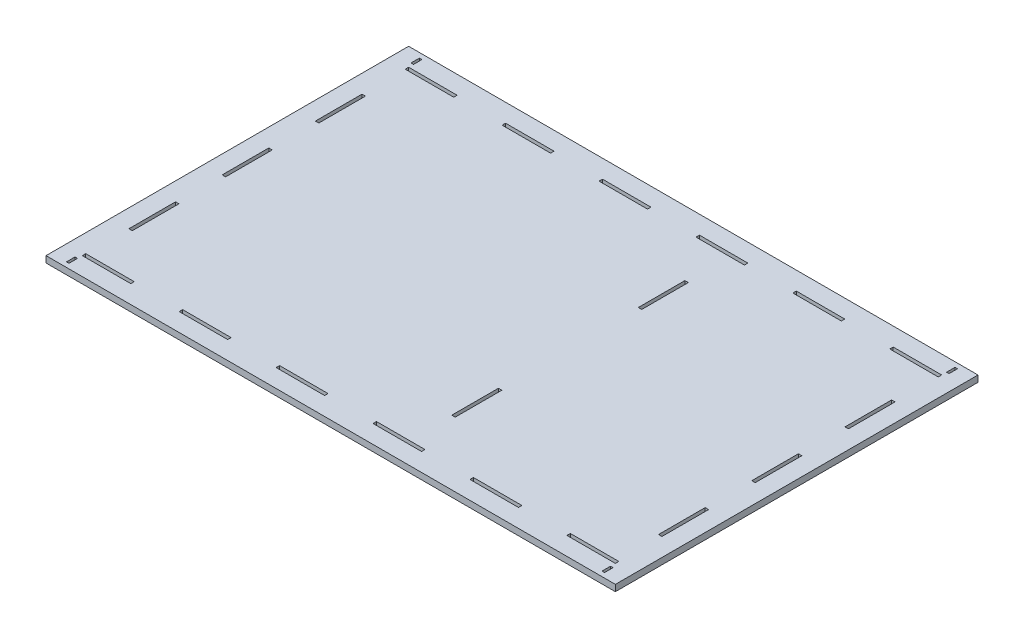
SolidWorks part; units mm, degrees
ref_plane "Front Plane" through (0, 0, 0) normal (0, 0, 1) x (1, 0, 0)
ref_plane "Top Plane" through (0, 0, 0) normal (0, 1, 0) x (1, 0, 0)
ref_plane "Right Plane" through (0, 0, 0) normal (1, 0, 0) x (0, 0, -1)
sketch "Sketch2" plane through (0, 0, 0) normal (0, 1, 0) x (1, 0, 0)
  line L0 (-230.0986, 0) -> (230.0986, 0) construction
  line L1 (-230.0986, 139.7) -> (230.0986, 139.7)
  line L2 (-230.0986, 139.7) -> (-230.0986, -139.7)
  line L3 (-230.0986, -139.7) -> (230.0986, -139.7)
  line L4 (230.0986, 139.7) -> (230.0986, -139.7)
  line L5 (0, 139.7) -> (0, -139.7) construction
  line L6 (-148.3337, -139.7) -> (-148.3337, -142.6972)
  line L15 (-230.0986, 142.6972) -> (-233.0958, 142.6972)
  line L16 (-230.0986, 142.6972) -> (-230.0986, 101.9266)
  line L17 (-230.0986, 101.9266) -> (-233.0958, 101.9266)
  line L18 (-233.0958, 142.6972) -> (-233.0958, 101.9266)
  line L19 (230.0986, 101.9266) -> (233.0958, 101.9266)
  line L20 (230.0986, 101.9266) -> (230.0986, 142.6972)
  line L21 (230.0986, 142.6972) -> (233.0958, 142.6972)
  line L22 (233.0958, 101.9266) -> (233.0958, 142.6972)
  line L23 (-190.7147, -139.7) -> (-233.0958, -139.7)
  line L24 (-190.7147, -139.7) -> (-190.7147, -142.6972)
  line L25 (-190.7147, -142.6972) -> (-233.0958, -142.6972)
  line L26 (-233.0958, -139.7) -> (-233.0958, -142.6972)
  line L27 (-233.0958, 142.6972) -> (-190.7147, 142.6972)
  line L28 (-233.0958, 142.6972) -> (-233.0958, 139.7)
  line L29 (-233.0958, 139.7) -> (-190.7147, 139.7)
  line L30 (-190.7147, 142.6972) -> (-190.7147, 139.7)
  line L31 (-148.3337, -139.7) -> (-190.7147, -139.7)
  line L32 (-190.7147, -139.7) -> (-190.7147, -142.6972)
  line L33 (-148.3337, -142.6972) -> (-190.7147, -142.6972)
  line L34 (-190.7147, 142.6972) -> (-190.7147, 139.7)
  line L35 (-190.7147, 142.6972) -> (-148.3337, 142.6972)
  line L36 (-148.3337, 142.6972) -> (-148.3337, 139.7)
  line L37 (-190.7147, 139.7) -> (-148.3337, 139.7)
  line L38 (-105.9526, -139.7) -> (-105.9526, -142.6972)
  line L39 (-105.9526, -139.7) -> (-148.3337, -139.7)
  line L40 (-148.3337, -139.7) -> (-148.3337, -142.6972)
  line L41 (-105.9526, -142.6972) -> (-148.3337, -142.6972)
  line L42 (-148.3337, 142.6972) -> (-148.3337, 139.7)
  line L43 (-148.3337, 142.6972) -> (-105.9526, 142.6972)
  line L44 (-105.9526, 142.6972) -> (-105.9526, 139.7)
  line L45 (-148.3337, 139.7) -> (-105.9526, 139.7)
  line L46 (-63.5716, -139.7) -> (-63.5716, -142.6972)
  line L47 (-63.5716, -139.7) -> (-105.9526, -139.7)
  line L48 (-105.9526, -139.7) -> (-105.9526, -142.6972)
  line L49 (-63.5716, -142.6972) -> (-105.9526, -142.6972)
  line L50 (-105.9526, 142.6972) -> (-105.9526, 139.7)
  line L51 (-105.9526, 142.6972) -> (-63.5716, 142.6972)
  line L52 (-63.5716, 142.6972) -> (-63.5716, 139.7)
  line L53 (-105.9526, 139.7) -> (-63.5716, 139.7)
  line L54 (-21.1905, -139.7) -> (-21.1905, -142.6972)
  line L55 (-21.1905, -139.7) -> (-63.5716, -139.7)
  line L56 (-63.5716, -139.7) -> (-63.5716, -142.6972)
  line L57 (-21.1905, -142.6972) -> (-63.5716, -142.6972)
  line L58 (-63.5716, 142.6972) -> (-63.5716, 139.7)
  line L59 (-63.5716, 142.6972) -> (-21.1905, 142.6972)
  line L60 (-21.1905, 142.6972) -> (-21.1905, 139.7)
  line L61 (-63.5716, 139.7) -> (-21.1905, 139.7)
  line L62 (21.1905, -139.7) -> (21.1905, -142.6972)
  line L63 (21.1905, -139.7) -> (-21.1905, -139.7)
  line L64 (-21.1905, -139.7) -> (-21.1905, -142.6972)
  line L65 (21.1905, -142.6972) -> (-21.1905, -142.6972)
  line L66 (-21.1905, 142.6972) -> (-21.1905, 139.7)
  line L67 (-21.1905, 142.6972) -> (21.1905, 142.6972)
  line L68 (21.1905, 142.6972) -> (21.1905, 139.7)
  line L69 (-21.1905, 139.7) -> (21.1905, 139.7)
  line L70 (63.5716, -139.7) -> (63.5716, -142.6972)
  line L71 (63.5716, -139.7) -> (21.1905, -139.7)
  line L72 (21.1905, -139.7) -> (21.1905, -142.6972)
  line L73 (63.5716, -142.6972) -> (21.1905, -142.6972)
  line L74 (21.1905, 142.6972) -> (21.1905, 139.7)
  line L75 (21.1905, 142.6972) -> (63.5716, 142.6972)
  line L76 (63.5716, 142.6972) -> (63.5716, 139.7)
  line L77 (21.1905, 139.7) -> (63.5716, 139.7)
  line L78 (105.9526, -139.7) -> (105.9526, -142.6972)
  line L79 (105.9526, -139.7) -> (63.5716, -139.7)
  line L80 (63.5716, -139.7) -> (63.5716, -142.6972)
  line L81 (105.9526, -142.6972) -> (63.5716, -142.6972)
  line L82 (63.5716, 142.6972) -> (63.5716, 139.7)
  line L83 (63.5716, 142.6972) -> (105.9526, 142.6972)
  line L84 (105.9526, 142.6972) -> (105.9526, 139.7)
  line L85 (63.5716, 139.7) -> (105.9526, 139.7)
  line L86 (148.3337, -139.7) -> (148.3337, -142.6972)
  line L87 (148.3337, -139.7) -> (105.9526, -139.7)
  line L88 (105.9526, -139.7) -> (105.9526, -142.6972)
  line L89 (148.3337, -142.6972) -> (105.9526, -142.6972)
  line L90 (105.9526, 142.6972) -> (105.9526, 139.7)
  line L91 (105.9526, 142.6972) -> (148.3337, 142.6972)
  line L92 (148.3337, 142.6972) -> (148.3337, 139.7)
  line L93 (105.9526, 139.7) -> (148.3337, 139.7)
  line L94 (190.7147, -139.7) -> (190.7147, -142.6972)
  line L95 (190.7147, -139.7) -> (148.3337, -139.7)
  line L96 (148.3337, -139.7) -> (148.3337, -142.6972)
  line L97 (190.7147, -142.6972) -> (148.3337, -142.6972)
  line L98 (148.3337, 142.6972) -> (148.3337, 139.7)
  line L99 (148.3337, 142.6972) -> (190.7147, 142.6972)
  line L100 (190.7147, 142.6972) -> (190.7147, 139.7)
  line L101 (148.3337, 139.7) -> (190.7147, 139.7)
  line L102 (233.0958, -139.7) -> (233.0958, -142.6972)
  line L103 (233.0958, -139.7) -> (190.7147, -139.7)
  line L104 (190.7147, -139.7) -> (190.7147, -142.6972)
  line L105 (233.0958, -142.6972) -> (190.7147, -142.6972)
  line L106 (190.7147, 142.6972) -> (190.7147, 139.7)
  line L107 (190.7147, 142.6972) -> (233.0958, 142.6972)
  line L108 (233.0958, 142.6972) -> (233.0958, 139.7)
  line L109 (190.7147, 139.7) -> (233.0958, 139.7)
  line L110 (-233.0958, 101.9266) -> (-233.0958, 61.1559)
  line L111 (-230.0986, 101.9266) -> (-230.0986, 61.1559)
  line L112 (-230.0986, 101.9266) -> (-233.0958, 101.9266)
  line L113 (-230.0986, 61.1559) -> (-233.0958, 61.1559)
  line L114 (230.0986, 61.1559) -> (230.0986, 101.9266)
  line L115 (230.0986, 61.1559) -> (233.0958, 61.1559)
  line L116 (233.0958, 61.1559) -> (233.0958, 101.9266)
  line L117 (230.0986, 101.9266) -> (233.0958, 101.9266)
  line L118 (-233.0958, 61.1559) -> (-233.0958, 20.3853)
  line L119 (-230.0986, 61.1559) -> (-230.0986, 20.3853)
  line L120 (-230.0986, 61.1559) -> (-233.0958, 61.1559)
  line L121 (-230.0986, 20.3853) -> (-233.0958, 20.3853)
  line L122 (230.0986, 20.3853) -> (230.0986, 61.1559)
  line L123 (230.0986, 20.3853) -> (233.0958, 20.3853)
  line L124 (233.0958, 20.3853) -> (233.0958, 61.1559)
  line L125 (230.0986, 61.1559) -> (233.0958, 61.1559)
  line L126 (-233.0958, 20.3853) -> (-233.0958, -20.3853)
  line L127 (-230.0986, 20.3853) -> (-230.0986, -20.3853)
  line L128 (-230.0986, 20.3853) -> (-233.0958, 20.3853)
  line L129 (-230.0986, -20.3853) -> (-233.0958, -20.3853)
  line L130 (230.0986, -20.3853) -> (230.0986, 20.3853)
  line L131 (230.0986, -20.3853) -> (233.0958, -20.3853)
  line L132 (233.0958, -20.3853) -> (233.0958, 20.3853)
  line L133 (230.0986, 20.3853) -> (233.0958, 20.3853)
  line L134 (-233.0958, -20.3853) -> (-233.0958, -61.1559)
  line L135 (-230.0986, -20.3853) -> (-230.0986, -61.1559)
  line L136 (-230.0986, -20.3853) -> (-233.0958, -20.3853)
  line L137 (-230.0986, -61.1559) -> (-233.0958, -61.1559)
  line L138 (230.0986, -61.1559) -> (230.0986, -20.3853)
  line L139 (230.0986, -61.1559) -> (233.0958, -61.1559)
  line L140 (233.0958, -61.1559) -> (233.0958, -20.3853)
  line L141 (230.0986, -20.3853) -> (233.0958, -20.3853)
  line L142 (-233.0958, -61.1559) -> (-233.0958, -101.9266)
  line L143 (-230.0986, -61.1559) -> (-230.0986, -101.9266)
  line L144 (-230.0986, -61.1559) -> (-233.0958, -61.1559)
  line L145 (-230.0986, -101.9266) -> (-233.0958, -101.9266)
  line L146 (230.0986, -101.9266) -> (230.0986, -61.1559)
  line L147 (230.0986, -101.9266) -> (233.0958, -101.9266)
  line L148 (233.0958, -101.9266) -> (233.0958, -61.1559)
  line L149 (230.0986, -61.1559) -> (233.0958, -61.1559)
  line L150 (-233.0958, -101.9266) -> (-233.0958, -142.6972)
  line L151 (-230.0986, -101.9266) -> (-230.0986, -142.6972)
  line L152 (-230.0986, -101.9266) -> (-233.0958, -101.9266)
  line L153 (-230.0986, -142.6972) -> (-233.0958, -142.6972)
  line L154 (230.0986, -142.6972) -> (230.0986, -101.9266)
  line L155 (230.0986, -142.6972) -> (233.0958, -142.6972)
  line L156 (233.0958, -142.6972) -> (233.0958, -101.9266)
  line L157 (230.0986, -101.9266) -> (233.0958, -101.9266)
  point P9 (0, 0)
  dimension "D1" = 279.4
  dimension "D2" = 460.1972
  dimension "D3" = 466.1916
  dimension "D4" = 285.3944
  dimension "D6" = 42.3811
  dimension "D8" = 40.7706
  dimension "D5" = 11
  dimension "D7" = 7
extrude "Boss-Extrude1" add sketch "Sketch2" along normal blind 5.588 contours L4 L1 L2 L3 | L36 L35 L30 L1 | L29 L18 L17 L2 | L121 L2 L113 L118 | L137 L2 L129 L134 | L52 L51 L44 L1 | L68 L67 L60 L1 | L84 L83 L76 L1 | L100 L99 L92 L1 | L97 L94 L3 L86 | L81 L78 L3 L70 | L65 L62 L3 L54 | L49 L46 L3 L38 | L33 L6 L3 L24 | L145 L150 L23 L2 | L103 L156 L147 L4 | L139 L140 L131 L4 | L123 L124 L115 L4 | L109 L4 L19 L22
sketch "Sketch3" plane through (0, 5.588, 0) normal (0, 1, 0) x (1, 0, 0)
  line L0 (50.8, -61.1559) -> (50.8, 61.1559) construction
  line L1 (49.3014, 101.9266) -> (52.2986, 101.9266)
  line L2 (49.3014, 101.9266) -> (49.3014, 61.1559)
  line L3 (49.3014, 61.1559) -> (52.2986, 61.1559)
  line L4 (52.2986, 101.9266) -> (52.2986, 61.1559)
  line L5 (49.3014, -101.9266) -> (52.2986, -101.9266)
  line L6 (49.3014, -101.9266) -> (49.3014, -61.1559)
  line L7 (49.3014, -61.1559) -> (52.2986, -61.1559)
  line L8 (52.2986, -101.9266) -> (52.2986, -61.1559)
  line L9 (0, 0) -> (50.8, 0) construction
  line L10 (-230.0986, 101.9266) -> (-233.0958, 101.9266) construction
  line L12 (52.2986, -101.9266) -> (49.3014, -101.9266)
  line L13 (52.2986, -101.9266) -> (52.2986, -142.6972)
  line L14 (52.2986, -142.6972) -> (49.3014, -142.6972)
  line L15 (49.3014, -101.9266) -> (49.3014, -142.6972)
  line L17 (52.2986, 101.9266) -> (49.3014, 101.9266)
  line L18 (52.2986, 101.9266) -> (52.2986, 142.6972)
  line L19 (52.2986, 142.6972) -> (49.3014, 142.6972)
  line L20 (49.3014, 101.9266) -> (49.3014, 142.6972)
  line L21 (-230.0986, -61.1559) -> (-230.0986, -101.9266) construction
  line L22 (-230.0986, 101.9266) -> (-230.0986, 61.1559) construction
  dimension "D1" = 279.4
extrude "Cut-Extrude1" cut sketch "Sketch3" against normal through all contours L5 L8 L7 L6 | L4 L1 L2 L3
sketch "Sketch4" plane through (0, 5.588, 0) normal (0, 1, 0) x (1, 0, 0)
  line L0 (-233.0958, 139.7) -> (-233.0958, 101.9266) construction
  line L1 (-233.0958, 158.5722) -> (-248.9708, 158.5722)
  line L2 (-233.0958, 158.5722) -> (-233.0958, -158.5722)
  line L3 (-233.0958, -158.5722) -> (-248.9708, -158.5722)
  line L4 (-248.9708, 158.5722) -> (-248.9708, -158.5722)
  line L5 (148.3337, 142.6972) -> (190.7147, 142.6972) construction
  line L6 (-233.0958, 158.5722) -> (233.0958, 158.5722)
  line L7 (-233.0958, 158.5722) -> (-233.0958, 142.6972)
  line L8 (-233.0958, 142.6972) -> (233.0958, 142.6972)
  line L9 (233.0958, 158.5722) -> (233.0958, 142.6972)
  line L10 (-228.0134, -142.6972) -> (-228.0134, -158.5722) construction
  line L15 (190.7147, -142.6972) -> (148.3337, -142.6972) construction
  line L16 (-233.0958, -158.5722) -> (233.0958, -158.5722)
  line L17 (-233.0958, -158.5722) -> (-233.0958, -142.6972)
  line L18 (-233.0958, -142.6972) -> (233.0958, -142.6972)
  line L19 (233.0958, -158.5722) -> (233.0958, -142.6972)
  line L20 (233.0958, 101.9266) -> (233.0958, 139.7) construction
  line L21 (233.0958, 158.5722) -> (248.9708, 158.5722)
  line L22 (233.0958, 158.5722) -> (233.0958, -158.5722)
  line L23 (233.0958, -158.5722) -> (248.9708, -158.5722)
  line L24 (248.9708, 158.5722) -> (248.9708, -158.5722)
  line L25 (-248.9708, 0) -> (248.9708, 0) construction
  line L26 (-228.0134, -150.6347) -> (-235.2958, -150.6347) construction
  line L27 (-235.2958, -146.92) -> (-233.0958, -146.92)
  line L28 (-235.2958, -146.92) -> (-235.2958, -154.3494)
  line L29 (-235.2958, -154.3494) -> (-233.0958, -154.3494)
  line L30 (-233.0958, -146.92) -> (-233.0958, -154.3494)
  line L32 (-234.1958, 146.92) -> (-234.1958, -146.92) construction
  line L33 (-233.0958, 154.3494) -> (-235.2958, 154.3494)
  line L34 (-233.0958, 154.3494) -> (-233.0958, 146.92)
  line L35 (-233.0958, 146.92) -> (-235.2958, 146.92)
  line L36 (-235.2958, 154.3494) -> (-235.2958, 146.92)
  line L37 (0, -3.0734) -> (0, 3.0734) construction
  line L38 (233.0958, 146.92) -> (235.2958, 146.92)
  line L39 (235.2958, 154.3494) -> (235.2958, 146.92)
  line L40 (233.0958, 154.3494) -> (235.2958, 154.3494)
  line L41 (233.0958, 154.3494) -> (233.0958, 146.92)
  line L42 (235.2958, -154.3494) -> (233.0958, -154.3494)
  line L43 (233.0958, -146.92) -> (233.0958, -154.3494)
  line L44 (235.2958, -146.92) -> (233.0958, -146.92)
  line L45 (235.2958, -146.92) -> (235.2958, -154.3494)
  point P12 (0, 0)
  point P39 (-234.1958, 0)
  dimension "D1" = 15.875
  dimension "D2" = 15.875
  dimension "D3" = 2.2
  dimension "D4" = 7.4295
extrude "Boss-Extrude2" add sketch "Sketch4" against normal up to surface (5.588 mm away) contours L9 L6 L2 L8 | L4 L25 L2 L1 | L16 L19 L18 L2 | L25 L22 L19 L23 L24
equation "\"wallthickness\"= .118in"
equation "\"floorThickness\"= .220in"
equation "\"D2@Sketch2\"=11+7+\"wallthickness\""
equation "\"D3@Sketch2\"=\"wallthickness\"*2+\"D2@Sketch2\""
equation "\"D4@Sketch2\"=\"wallthickness\"*2+\"D1@Sketch2\""
equation "\"D6@Sketch2\"=\"D3@Sketch2\"/\"D5@Sketch2\""
equation "\"D8@Sketch2\"=\"D4@Sketch2\"/\"D7@Sketch2\""
equation "\"D1@Boss-Extrude1\"=\"floorThickness\""
equation "\"D2@Sketch4\"=\"D1@Sketch4\""
